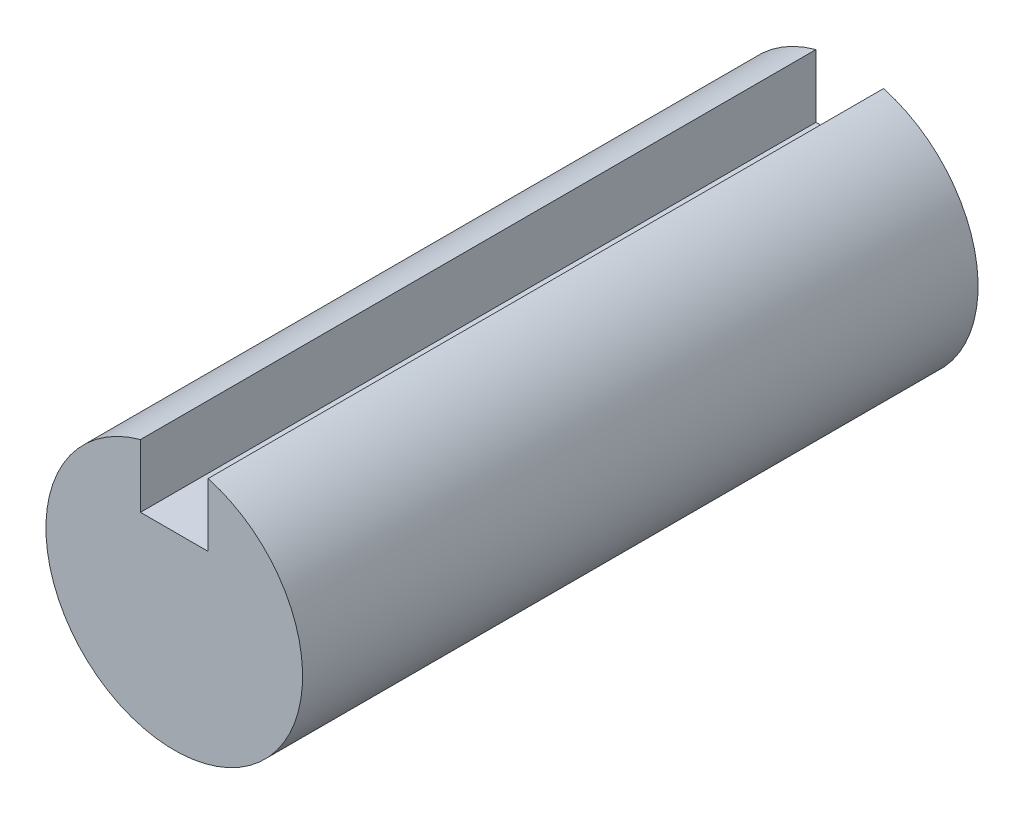
SolidWorks part; units mm, degrees
ref_plane "Front Plane" through (0, 0, 0) normal (0, 0, 1) x (1, 0, 0)
ref_plane "Top Plane" through (0, 0, 0) normal (0, 1, 0) x (1, 0, 0)
ref_plane "Right Plane" through (0, 0, 0) normal (1, 0, 0) x (0, 0, -1)
sketch "Sketch1" plane through (0, 0, 0) normal (0, 0, 1) x (1, 0, 0)
  circle A0 centre (0, 0) radius 9.5
  dimension "D1" = 19
extrude "Boss-Extrude1" add sketch "Sketch1" along normal blind 50
sketch "Sketch2" plane through (0, 0, 50) normal (0, 0, 1) x (1, 0, 0)
  line L1 (2.5, 14.5) -> (-2.5, 14.5)
  line L2 (2.5, 14.5) -> (2.5, 4.5)
  line L3 (2.5, 4.5) -> (-2.5, 4.5)
  line L4 (-2.5, 14.5) -> (-2.5, 4.5)
  line L5 (2.5, 14.5) -> (-2.5, 4.5) construction
  line L6 (2.5, 4.5) -> (-2.5, 14.5) construction
  circle A0 centre (0, 0) radius 9.5 construction
  point P0 (0, 9.5)
  dimension "D1" = 5
  dimension "D2" = 10
extrude "Cut-Extrude1" cut sketch "Sketch2" against normal through all
